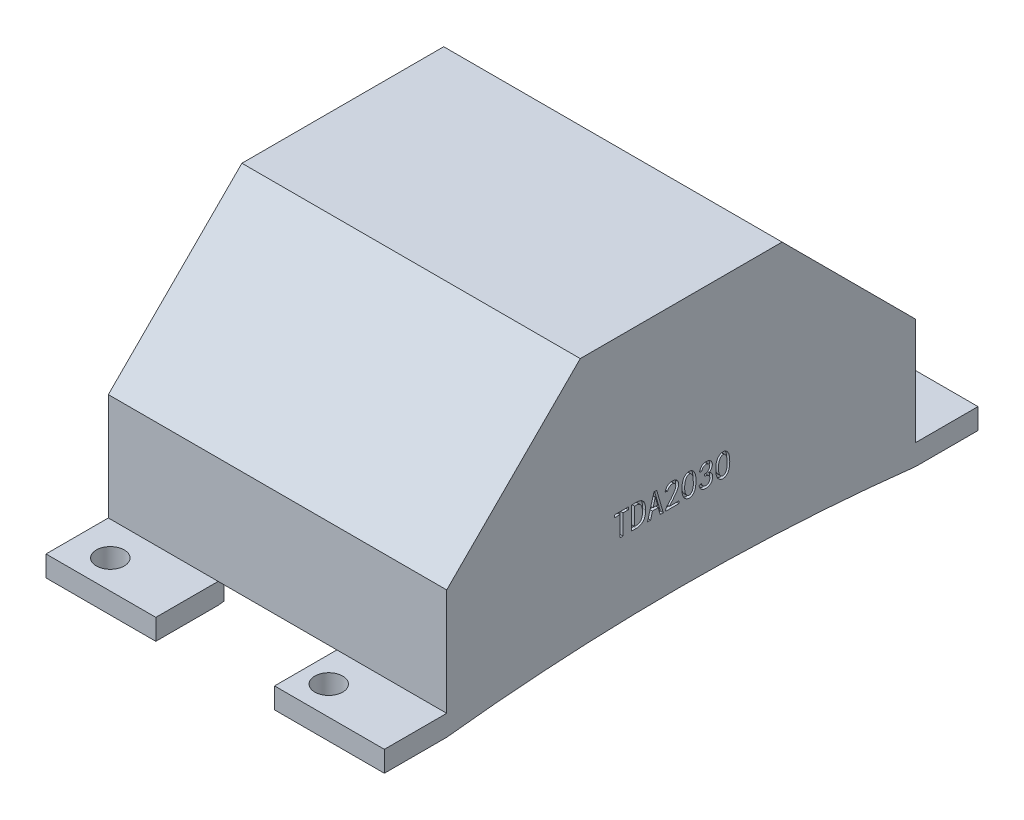
SolidWorks part; units mm, degrees
ref_plane "前视基准面" through (0, 0, 0) normal (0, 0, 1) x (1, 0, 0)
ref_plane "上视基准面" through (0, 0, 0) normal (0, 1, 0) x (1, 0, 0)
ref_plane "右视基准面" through (0, 0, 0) normal (1, 0, 0) x (0, 0, -1)
sketch "草图1" plane through (0, 0, 0) normal (0, 0, 1) x (1, 0, 0)
  line L0 (-10, -18.5) -> (-10, -22)
  line L1 (-28.5, -22) -> (-10, -22)
  line L2 (-28.5, -22) -> (-28.5, 22)
  line L3 (-28.5, 22) -> (28.5, 22)
  line L4 (28.5, -22) -> (28.5, 22)
  line L5 (-28.5, -22) -> (28.5, 22) construction
  line L6 (-28.5, 22) -> (28.5, -22) construction
  line L7 (-25.5, 20) -> (25.5, 20)
  line L8 (-25.5, 20) -> (-25.5, -18.5)
  line L9 (-25.5, -18.5) -> (-10, -18.5)
  line L10 (25.5, 20) -> (25.5, -18.5)
  line L11 (10, -18.5) -> (10, -22)
  line L12 (10, -18.5) -> (25.5, -18.5)
  line L13 (10, -22) -> (28.5, -22)
  point P0 (0, 0)
  point P14 (0, 22)
  point P15 (0, 20)
  point P16 (25.5, -19.7537)
  point P17 (-25.5, -17.7779)
  point P18 (-25.5, -19.8384)
  point P19 (25.5, -17.8767)
  dimension "D1" = 51
  dimension "D2" = 3
  dimension "D3" = 2
  dimension "D4" = 3.5
  dimension "D5" = 20
  dimension "D6" = 44
extrude "凸台-拉伸1" add sketch "草图1" along normal blind 100
sketch "草图2" plane through (0, -22, 0) normal (0, -1, 0) x (1, 0, 0)
  line L0 (-28.5, 100) -> (-28.5, 0) construction
  line L1 (-22.5, 95.17) -> (14.3, 95.17) construction
  line L2 (-22.5, 95.17) -> (-22.5, 4.83) construction
  line L3 (-22.5, 4.83) -> (14.3, 4.83) construction
  line L4 (14.3, 95.17) -> (14.3, 4.83) construction
  circle A0 centre (-22.5, 95.17) radius 2.35
  circle A1 centre (14.3, 95.17) radius 2.35
  circle A2 centre (14.3, 4.83) radius 2.35
  circle A3 centre (-22.5, 4.83) radius 2.35
  point P8 (-22.5, 50)
  point P11 (-28.5, 50)
  dimension "D3" = 4.7
  dimension "D1" = 36.8
  dimension "D2" = 90.34
  dimension "D4" = 6
extrude "切除-拉伸1" cut sketch "草图2" against normal through all
sketch "草图3" plane through (28.5, 0, 0) normal (1, 0, 0) x (0, 0, -1)
  line L0 (-100, -22) -> (0, -22) construction
  line L2 (-89.5, -22) -> (-10.5, -22)
  line L3 (-100, 22) -> (-67, 22)
  line L4 (-100, 22) -> (-100, -18.5)
  line L5 (-100, -18.5) -> (-89.5, -18.5)
  line L6 (-89.5, -0.5) -> (-89.5, -18.5)
  line L7 (-100, -18.5) -> (0, -18.5) construction
  line L8 (-100, 22) -> (0, 22) construction
  line L9 (0, 22) -> (-33, 22)
  line L11 (0, 22) -> (0, -18.5)
  line L12 (0, -18.5) -> (-10.5, -18.5)
  line L13 (-10.5, -0.5) -> (-10.5, -18.5)
  line L14 (-100, 22) -> (0, 22) construction
  line L15 (-33, 22) -> (-10.5, -0.5)
  line L16 (-67, 22) -> (-89.5, -0.5)
  arc A0 (-89.5, -22) -> (-10.5, -22) centre (-50, -367.3568) cw
  point P2 (0, 0)
  point P9 (-37.1703, 21.458)
  point P16 (-10.5, -5.2123)
  point P23 (-50, -22)
  point P24 (-50, 22)
  point P28 (-63.3881, 22)
  point P29 (0, 0)
  dimension "D2" = 135
  dimension "D1" = 79
  dimension "D3" = 135
  dimension "D4" = 18
  dimension "D5" = 34
extrude "切除-拉伸3" cut sketch "草图3" against normal through all
sketch "草图9" plane through (0, -22, 0) normal (0, -1, 0) x (1, 0, 0)
  line L0 (25.5, 89.5) -> (25.5, 10.5) construction
  line L1 (-25.5, 88.5) -> (25.5, 88.5)
  line L2 (-25.5, 88.5) -> (-25.5, 11.5)
  line L3 (-25.5, 11.5) -> (25.5, 11.5)
  line L4 (25.5, 88.5) -> (25.5, 11.5)
  line L5 (-25.5, 89.5) -> (-25.5, 10.5) construction
  line L6 (10, 89.5) -> (28.5, 89.5) construction
  line L7 (28.5, 10.5) -> (10, 10.5) construction
  point P6 (0, 0)
  point P9 (0, 0)
  dimension "D1" = 1
  dimension "D2" = 1
extrude "切除-拉伸4" cut sketch "草图9" against normal blind 9
sketch "草图5" plane through (0, 0, 10.5) normal (0, 0, -1) x (-1, 0, 0)
  line L1 (-28.5, -0.5) -> (28.5, -0.5)
  line L2 (-28.5, -0.5) -> (-28.5, -18.5)
  line L3 (-28.5, -18.5) -> (28.5, -18.5)
  line L4 (28.5, -0.5) -> (28.5, -18.5)
extrude "凸台-拉伸2" add sketch "草图5" against normal blind 1
sketch "草图6" plane through (0, -5.5, 5.5) normal (0, 0.7071, -0.7071) x (1, 0, 0)
  line L1 (28.5, -38.8909) -> (-28.5, -38.8909)
  line L2 (28.5, -38.8909) -> (28.5, -7.0711)
  line L3 (28.5, -7.0711) -> (-28.5, -7.0711)
  line L4 (-28.5, -38.8909) -> (-28.5, -7.0711)
extrude "凸台-拉伸3" add sketch "草图6" against normal blind 1
sketch "草图7" plane through (0, 0, 89.5) normal (0, 0, 1) x (1, 0, 0)
  line L1 (-28.5, -0.5) -> (28.5, -0.5)
  line L2 (-28.5, -0.5) -> (-28.5, -18.5)
  line L3 (-28.5, -18.5) -> (28.5, -18.5)
  line L4 (28.5, -0.5) -> (28.5, -18.5)
extrude "凸台-拉伸4" add sketch "草图7" against normal blind 1
sketch "草图8" plane through (0, 44.5, 44.5) normal (0, 0.7071, 0.7071) x (1, 0, 0)
  line L1 (-28.5, -31.8198) -> (28.5, -31.8198)
  line L2 (-28.5, -31.8198) -> (-28.5, -63.6396)
  line L3 (-28.5, -63.6396) -> (28.5, -63.6396)
  line L4 (28.5, -31.8198) -> (28.5, -63.6396)
extrude "凸台-拉伸5" add sketch "草图8" against normal blind 1
sketch "草图11" plane through (28.5, 0, 0) normal (1, 0, 0) x (0, 0, -1)
  text T0 "TDA2030" font "黑体" height 3.8
extrude "切除-拉伸5" cut sketch "草图11" against normal blind 0.5
